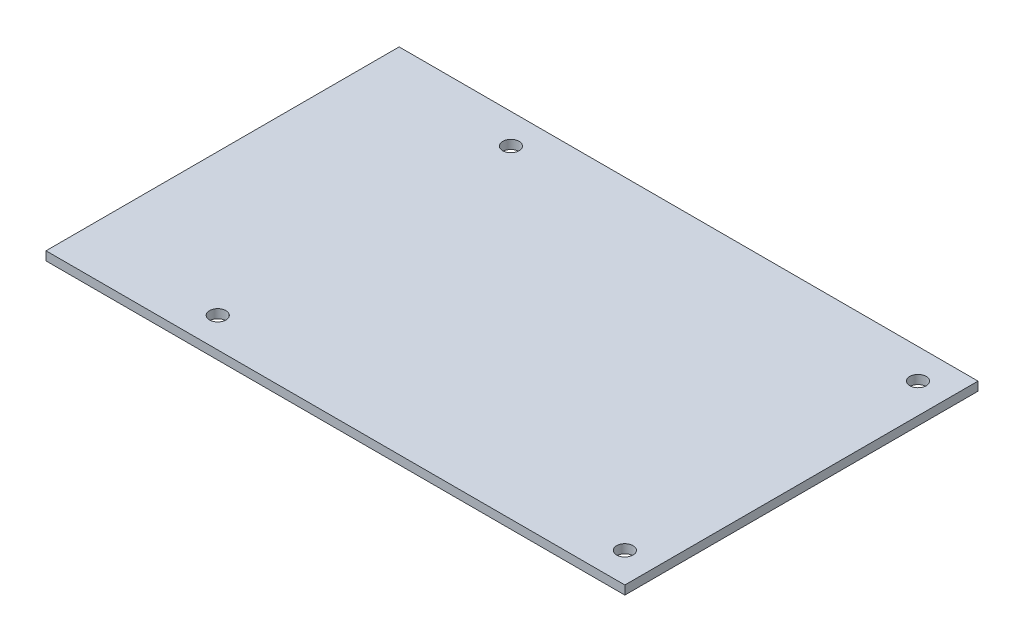
SolidWorks part; units mm, degrees
ref_plane "Front Plane" through (0, 0, 0) normal (0, 0, 1) x (1, 0, 0)
ref_plane "Top Plane" through (0, 0, 0) normal (0, 1, 0) x (1, 0, 0)
ref_plane "Right Plane" through (0, 0, 0) normal (1, 0, 0) x (0, 0, -1)
sketch "Sketch1" plane through (0, 0, 0) normal (0, 1, 0) x (1, 0, 0)
  line L1 (-53.086, -32.385) -> (53.086, -32.385)
  line L2 (-53.086, -32.385) -> (-53.086, 32.385)
  line L3 (-53.086, 32.385) -> (53.086, 32.385)
  line L4 (53.086, -32.385) -> (53.086, 32.385)
  line L5 (-53.086, -32.385) -> (53.086, 32.385) construction
  line L6 (-53.086, 32.385) -> (53.086, -32.385) construction
  point P0 (0, 0)
  dimension "D1" = 64.77
  dimension "D2" = 106.172
extrude "Boss-Extrude1" add sketch "Sketch1" along normal blind 1.6129
sketch "Sketch2" plane through (0, 1.6129, 0) normal (0, 1, 0) x (1, 0, 0)
  line L1 (53.086, -32.385) -> (53.086, 32.385) construction
  line L2 (53.086, 32.385) -> (-53.086, 32.385) construction
  line L3 (-53.086, -32.385) -> (53.086, -32.385) construction
  line L4 (-53.086, 32.385) -> (-53.086, -32.385) construction
  circle A1 centre (47.586, 26.885) radius 1.5
  circle A2 centre (47.586, -26.885) radius 1.5
  circle A3 centre (-27.086, -26.885) radius 1.5
  circle A4 centre (-27.086, 26.885) radius 1.5
  dimension "D1" = 5.5
  dimension "D5" = 3
  dimension "D7" = 3
  dimension "D9" = 3
  dimension "D2" = 5.5
  dimension "D3" = 5.5
  dimension "D4" = 5.5
  dimension "D6" = 26
  dimension "D8" = 5.5
  dimension "D10" = 5.5
  dimension "D11" = 26
extrude "Cut-Extrude1" cut sketch "Sketch2" against normal blind 1.6129
